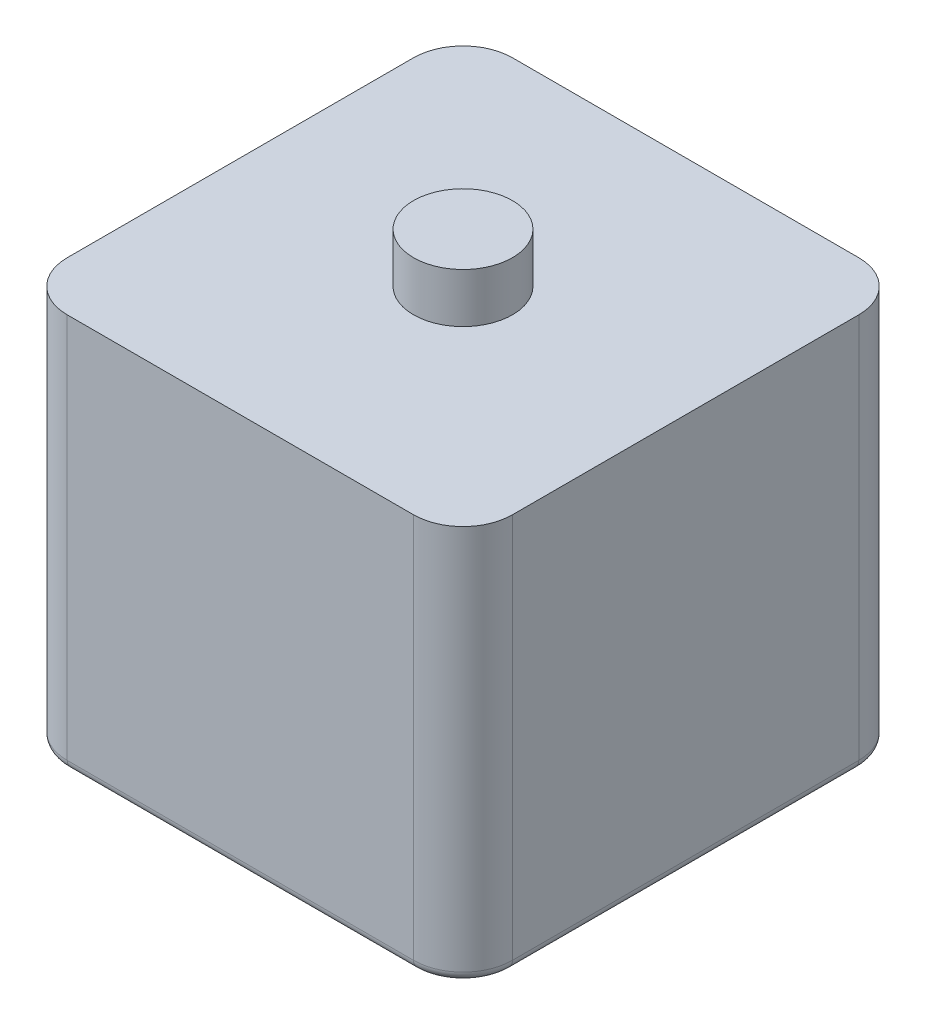
SolidWorks part; units mm, degrees
ref_plane "Alzado" through (0, 0, 0) normal (0, 0, 1) x (1, 0, 0)
ref_plane "Planta" through (0, 0, 0) normal (0, 1, 0) x (1, 0, 0)
ref_plane "Vista lateral" through (0, 0, 0) normal (1, 0, 0) x (0, 0, -1)
sketch "Croquis1" plane through (0, 0, 0) normal (0, 1, 0) x (1, 0, 0)
  line L1 (22.5, -22.5) -> (-22.5, -22.5)
  line L2 (22.5, -22.5) -> (22.5, 22.5)
  line L3 (22.5, 22.5) -> (-22.5, 22.5)
  line L4 (-22.5, -22.5) -> (-22.5, 22.5)
  line L5 (22.5, -22.5) -> (-22.5, 22.5) construction
  line L6 (22.5, 22.5) -> (-22.5, -22.5) construction
  point P0 (0, 0)
  dimension "D1" = 45
  dimension "D2" = 45
extrude "Extruir1" add sketch "Croquis1" along normal blind 40
sketch "Croquis2" plane through (0, 40, 0) normal (0, 1, 0) x (1, 0, 0)
  circle A0 centre (0, 0) radius 5
  dimension "D1" = 10
extrude "Extruir2" cut sketch "Croquis2" against normal blind 10
fillet "Redondeo1" radius 5 4 edges at (-22.5, 20, -22.5) (22.5, 20, -22.5) (22.5, 20, 22.5) (-22.5, 20, 22.5)
sketch "Croquis3" plane through (0, 0, 0) normal (0, -1, 0) x (1, 0, 0)
  circle A0 centre (0, 0) radius 15
  dimension "D1" = 30
extrude "Extruir3" add sketch "Croquis3" along normal blind 5
fillet "Redondeo2" radius 2 1 edges at (0, -5, -15)
fillet "Redondeo3" radius 1 9 edges at (0, 0, 15) (-21.0355, 0, 21.0355) (0, 0, 22.5) (21.0355, 0, 21.0355) (22.5, 0, 0) (21.0355, 0, -21.0355) (0, 0, -22.5) (-21.0355, 0, -21.0355) (-22.5, 0, 0)
sketch "Croquis4" plane through (0, -5, 0) normal (0, -1, 0) x (1, 0, 0)
  circle A0 centre (0, 0) radius 4
  dimension "D1" = 8
extrude "Extruir4" cut sketch "Croquis4" against normal blind 1
sketch "Croquis5" plane through (0, 40, 0) normal (0, 1, 0) x (1, 0, 0)
  circle A0 centre (0, 0) radius 5 construction
  circle A1 centre (0, 0) radius 5
extrude "Extruir5" add sketch "Croquis5" along normal blind 5 separate body
